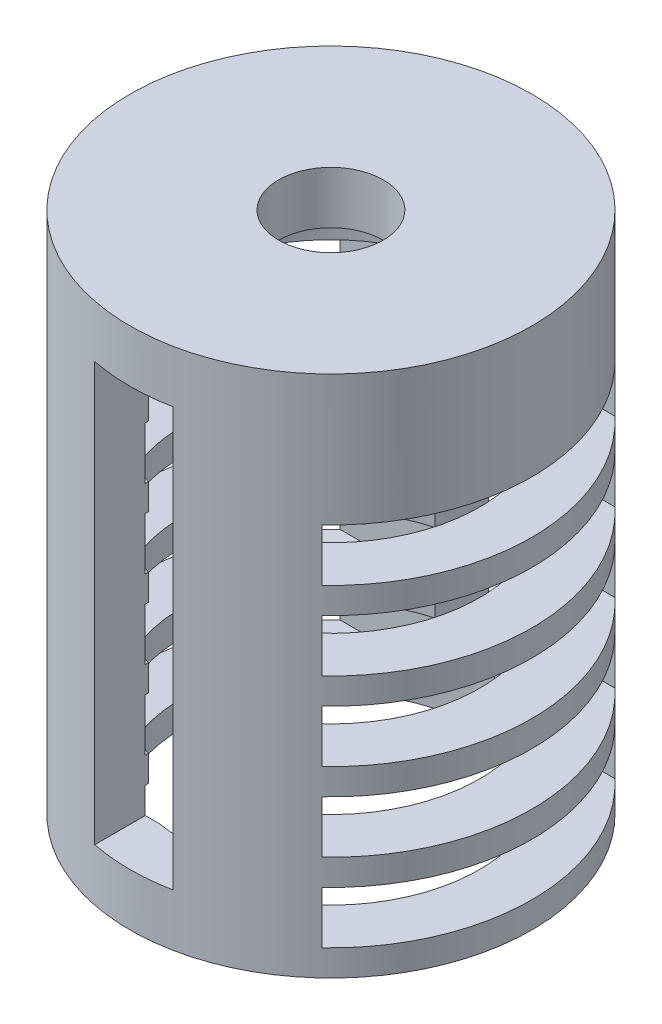
SolidWorks part; units mm, degrees
ref_plane "Front Plane" through (0, 0, 0) normal (0, 0, 1) x (1, 0, 0)
ref_plane "Top Plane" through (0, 0, 0) normal (0, 1, 0) x (1, 0, 0)
ref_plane "Right Plane" through (0, 0, 0) normal (1, 0, 0) x (0, 0, -1)
sketch "Sketch1" plane through (0, 0, 0) normal (0, 0, 1) x (1, 0, 0)
  line L0 (0, 0) -> (0, 495035.3938) construction
  line L1 (0, 0) -> (495035.3938, 0) construction
  line L2 (9.017, 15.875) -> (3.175, 15.875)
  line L3 (9.017, 15.875) -> (12.192, 15.875)
  line L4 (9.017, 15.875) -> (9.017, -15.875)
  line L5 (9.017, -15.875) -> (12.192, -15.875)
  line L6 (12.192, 15.875) -> (12.192, -15.875)
  line L7 (9.017, 15.875) -> (12.192, -15.875) construction
  line L8 (9.017, -15.875) -> (12.192, 15.875) construction
  line L9 (3.175, 15.875) -> (3.175, 12.7)
  line L10 (3.175, 12.7) -> (9.017, 12.7)
  point P6 (10.6045, 0)
  point P11 (6.096, 15.875)
  dimension "D1" = 9.017
  dimension "D2" = 3.175
  dimension "D3" = 31.75
  dimension "D4" = 3.175
  dimension "D5" = 3.175
revolve "Revolve1" add sketch "Sketch1" angle 360 about L0
sketch "Sketch2" plane through (0, 0, 0) normal (0, 0, 1) x (1, 0, 0)
  line L1 (2.3812, 12.7) -> (-2.3813, 12.7)
  line L2 (2.3812, 12.7) -> (2.3813, -12.7)
  line L3 (2.3813, -12.7) -> (-2.3812, -12.7)
  line L4 (-2.3813, 12.7) -> (-2.3812, -12.7)
  line L5 (2.3812, 12.7) -> (-2.3812, -12.7) construction
  line L6 (2.3813, -12.7) -> (-2.3813, 12.7) construction
  point P0 (0, 0)
  dimension "D1" = 4.7625
  dimension "D2" = 25.4
extrude "Cut-Extrude1" cut sketch "Sketch2" against normal mid plane 50.8
sketch "Sketch3" plane through (0, 0, 0) normal (1, 0, 0) x (0, 0, -1)
  line L0 (0, 0) -> (0, -50000) construction
  line L1 (-12.192, -15.875) -> (12.192, -15.875) construction
  line L2 (-8.89, -11.1125) -> (8.89, -11.1125)
  line L3 (-8.89, -11.1125) -> (-8.89, -14.2875)
  line L4 (-8.89, -14.2875) -> (8.89, -14.2875)
  line L5 (8.89, -11.1125) -> (8.89, -14.2875)
  line L6 (-8.89, -11.1125) -> (8.89, -14.2875) construction
  line L7 (-8.89, -14.2875) -> (8.89, -11.1125) construction
  line L8 (-12.192, -15.875) -> (12.192, -15.875) construction
  line L9 (-8.89, -6.35) -> (8.89, -6.35)
  line L10 (-8.89, -9.525) -> (8.89, -9.525)
  line L11 (8.89, -6.35) -> (8.89, -9.525)
  line L12 (-8.89, -6.35) -> (-8.89, -9.525)
  line L13 (-8.89, -1.5875) -> (8.89, -1.5875)
  line L14 (-8.89, -4.7625) -> (8.89, -4.7625)
  line L15 (8.89, -1.5875) -> (8.89, -4.7625)
  line L16 (-8.89, -1.5875) -> (-8.89, -4.7625)
  line L17 (-8.89, 3.175) -> (8.89, 3.175)
  line L18 (-8.89, 0) -> (8.89, 0)
  line L19 (8.89, 3.175) -> (8.89, 0)
  line L20 (-8.89, 3.175) -> (-8.89, 0)
  line L21 (-8.89, 7.9375) -> (8.89, 7.9375)
  line L22 (-8.89, 4.7625) -> (8.89, 4.7625)
  line L23 (8.89, 7.9375) -> (8.89, 4.7625)
  line L24 (-8.89, 7.9375) -> (-8.89, 4.7625)
  point P3 (0, -12.7)
  dimension "D1" = 17.78
  dimension "D2" = 3.175
  dimension "D3" = 1.5875
  dimension "D4" = 5
extrude "Cut-Extrude2" cut sketch "Sketch3" against normal mid plane 50.8
